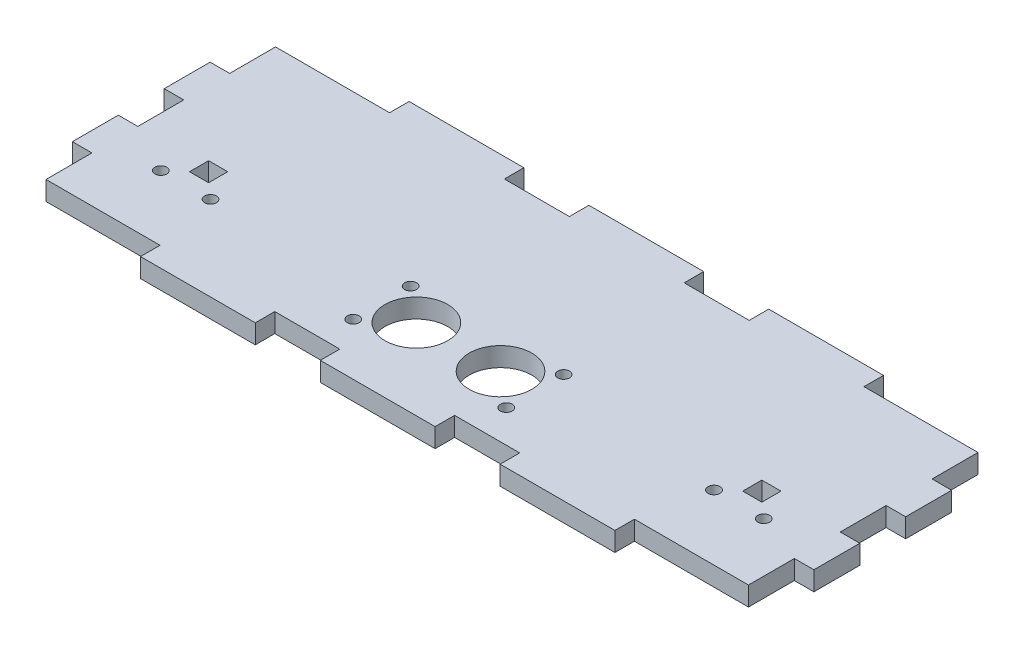
SolidWorks part; units mm, degrees
ref_plane "Front Plane" through (0, 0, 0) normal (0, 0, 1) x (1, 0, 0)
ref_plane "Top Plane" through (0, 0, 0) normal (0, 1, 0) x (1, 0, 0)
ref_plane "Right Plane" through (0, 0, 0) normal (1, 0, 0) x (0, 0, -1)
sketch "Sketch1" plane through (0, 0, 0) normal (0, 1, 0) x (1, 0, 0)
  line L1 (-87.4145, -48) -> (-57.6145, -48)
  line L2 (-57.6145, -48) -> (-57.6145, -53.1)
  line L3 (-57.6145, -53.1) -> (-27.6145, -53.1)
  line L4 (-27.6145, -53.1) -> (-27.6145, -48)
  line L5 (-27.6145, -48) -> (-10.6145, -48)
  line L6 (-10.6145, -48) -> (-10.6145, -53.1)
  line L7 (-10.6145, -53.1) -> (19.3855, -53.1)
  line L8 (19.3855, -53.1) -> (19.3855, -48)
  line L9 (19.3855, -48) -> (36.3855, -48)
  line L10 (36.3855, -48) -> (36.3855, -53.1)
  line L11 (36.3855, -53.1) -> (66.3855, -53.1)
  line L12 (66.3855, -53.1) -> (66.3855, -48)
  line L13 (66.3855, -48) -> (96.1855, -48)
  line L18 (66.3855, 12) -> (96.1855, 12)
  line L19 (66.3855, 17.1) -> (66.3855, 12)
  line L20 (36.3855, 12) -> (36.3855, 17.1)
  line L21 (-10.6145, 17.1) -> (19.3855, 17.1)
  line L22 (36.3855, 17.1) -> (66.3855, 17.1)
  line L23 (19.3855, 12) -> (36.3855, 12)
  line L24 (19.3855, 17.1) -> (19.3855, 12)
  line L25 (-10.6145, 12) -> (-10.6145, 17.1)
  line L26 (-27.6145, 12) -> (-10.6145, 12)
  line L27 (-27.6145, 17.1) -> (-27.6145, 12)
  line L28 (-57.6145, 17.1) -> (-27.6145, 17.1)
  line L29 (-57.6145, 12) -> (-57.6145, 17.1)
  line L30 (-87.4145, 12) -> (-57.6145, 12)
  line L31 (-87.4145, -48) -> (-87.4145, -36)
  line L32 (-87.4145, -36) -> (-92.5145, -36)
  line L33 (-92.5145, -36) -> (-92.5145, -24)
  line L34 (-92.5145, -24) -> (-87.4145, -24)
  line L35 (-87.4145, -24) -> (-87.4145, -12)
  line L36 (-87.4145, -12) -> (-92.5145, -12)
  line L37 (-92.5145, -12) -> (-92.5145, 0)
  line L38 (-92.5145, 0) -> (-87.4145, 0)
  line L39 (-87.4145, 0) -> (-87.4145, 12)
  line L40 (4.3855, 17.1) -> (4.3855, 3.0395) construction
  line L41 (96.1855, 0) -> (96.1855, 12)
  line L42 (101.2855, 0) -> (96.1855, 0)
  line L43 (101.2855, -12) -> (101.2855, 0)
  line L44 (96.1855, -12) -> (101.2855, -12)
  line L45 (96.1855, -24) -> (96.1855, -12)
  line L46 (101.2855, -24) -> (96.1855, -24)
  line L47 (101.2855, -36) -> (101.2855, -24)
  line L48 (96.1855, -36) -> (101.2855, -36)
  line L49 (96.1855, -48) -> (96.1855, -36)
  line L50 (-70.4145, -22.5) -> (-65.4145, -22.5)
  line L51 (-70.4145, -22.5) -> (-70.4145, -27.5)
  line L52 (-70.4145, -27.5) -> (-65.4145, -27.5)
  line L53 (-65.4145, -22.5) -> (-65.4145, -27.5)
  line L54 (79.1855, -27.5) -> (74.1855, -27.5)
  line L55 (74.1855, -22.5) -> (74.1855, -27.5)
  line L56 (79.1855, -22.5) -> (74.1855, -22.5)
  line L57 (79.1855, -22.5) -> (79.1855, -27.5)
  circle A2 centre (15.3855, -32) radius 8.2
  circle A3 centre (-6.6145, -32) radius 8.2
  circle A4 centre (-15.6145, -24.5) radius 1.55
  circle A5 centre (-15.6145, -39.5) radius 1.55
  circle A6 centre (-74.4145, -31) radius 1.55
  circle A7 centre (-61.4145, -31) radius 1.55
  circle A8 centre (24.3855, -39.5) radius 1.55
  circle A9 centre (24.3855, -24.5) radius 1.55
  circle A10 centre (70.1855, -31) radius 1.55
  circle A11 centre (83.1855, -31) radius 1.55
  dimension "D45" = 22
  dimension "D22" = 16.4
  dimension "D44" = 16.4
  dimension "D49" = 9
  dimension "D51" = 15
  dimension "D52" = 13
  dimension "D54" = 13
  dimension "D2" = 29.8
  dimension "D3" = 5.1
  dimension "D4" = 30
  dimension "D5" = 5.1
  dimension "D6" = 17
  dimension "D7" = 5.1
  dimension "D8" = 30
  dimension "D9" = 5.1
  dimension "D10" = 17
  dimension "D11" = 5.1
  dimension "D12" = 30
  dimension "D13" = 5.1
  dimension "D14" = 29.8
  dimension "D15" = 60
  dimension "D16" = 5.1
  dimension "D17" = 12
  dimension "D18" = 12
  dimension "D19" = 12
  dimension "D20" = 12
  dimension "D21" = 12
  dimension "D23" = 29.8
  dimension "D24" = 5.1
  dimension "D25" = 30
  dimension "D26" = 5.1
  dimension "D27" = 17
  dimension "D28" = 5.1
  dimension "D29" = 30
  dimension "D30" = 5.1
  dimension "D31" = 17
  dimension "D32" = 5.1
  dimension "D33" = 30
  dimension "D34" = 5.1
  dimension "D35" = 29.8
  dimension "D36" = 12
  dimension "D37" = 12
  dimension "D38" = 5.1
  dimension "D39" = 5.1
  dimension "D40" = 12
  dimension "D41" = 12
  dimension "D42" = 5.1
  dimension "D43" = 12
  dimension "D46" = 85.9
  dimension "D47" = 16
  dimension "D48" = 5.1
  dimension "D50" = 7.5
  dimension "D53" = 5
  dimension "D55" = 5
  dimension "D56" = 5
  dimension "D57" = 4
  dimension "D58" = 3.5
extrude "Boss-Extrude1" add sketch "Sketch1" along normal blind 5
